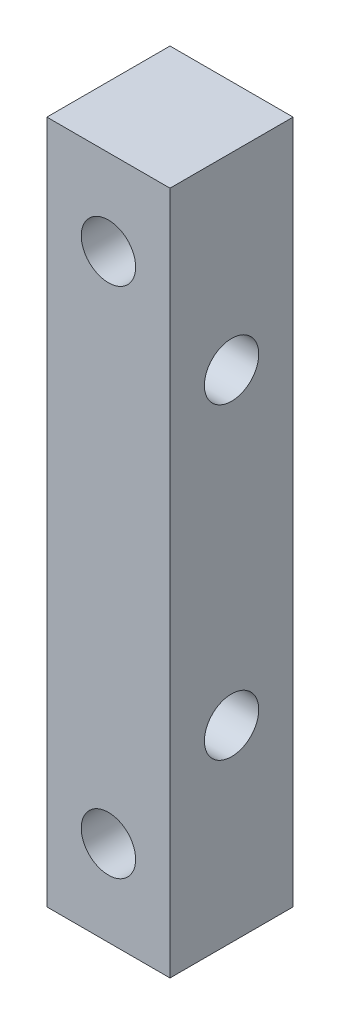
SolidWorks part; units mm, degrees
ref_plane "Front Plane" through (0, 0, 0) normal (0, 0, 1) x (1, 0, 0)
ref_plane "Top Plane" through (0, 0, 0) normal (0, 1, 0) x (1, 0, 0)
ref_plane "Right Plane" through (0, 0, 0) normal (1, 0, 0) x (0, 0, -1)
sketch "Sketch1" plane through (0, 0, 0) normal (0, 1, 0) x (1, 0, 0)
  line L1 (-4.572, 4.572) -> (4.572, 4.572)
  line L2 (-4.572, 4.572) -> (-4.572, -4.572)
  line L3 (-4.572, -4.572) -> (4.572, -4.572)
  line L4 (4.572, 4.572) -> (4.572, -4.572)
  line L5 (-4.572, 4.572) -> (4.572, -4.572) construction
  line L6 (-4.572, -4.572) -> (4.572, 4.572) construction
  point P0 (0, 0)
  dimension "D1" = 9.144
extrude "Boss-Extrude1" add sketch "Sketch1" along normal blind 50.8
sketch "Sketch3" plane through (0, 0, 4.572) normal (0, 0, 1) x (1, 0, 0)
  line L0 (0, 44.45) -> (0, 6.35) construction
  line L1 (4.572, 50.8) -> (4.572, 0) construction
  point P3 (0, 25.4)
  point P8 (4.572, 25.4)
  dimension "D1" = 38.1
hole_wizard "Tap Drill for #10-32 Tap1" positions "Sketch4" profile "Sketch6" hole size "#10-32" standard "ANSI Inch" end condition through all
sketch "Sketch4" plane through (0, 0, 4.572) normal (0, 0, 1) x (1, 0, 0)
  point P0 (0, 44.45)
  point P3 (0, 6.35)
sketch "Sketch6" plane through (0, 44.45, 4.572) normal (1, 0, 0) x (0, -1, 0)
  line L0 (0, 0) -> (0, 9.144)
  line L1 (0, 9.144) -> (2.0193, 9.144)
  line L2 (2.0193, 9.144) -> (2.0193, 0)
  line L5 (2.0193, 0) -> (0, 0)
  line L11 (0, -6.35) -> (0, 107.95) construction
  dimension "Thru Hole Dia." = 4.0386
  dimension "Thru Hole Depth" = 9.144
sketch "Sketch7" plane through (4.572, 0, 0) normal (1, 0, 0) x (0, 0, -1)
  line L0 (0, 36.83) -> (0, 13.97) construction
  line L1 (-4.572, 50.8) -> (-4.572, 0) construction
  line L2 (-4.572, 0) -> (4.572, 0) construction
  point P2 (-4.572, 25.4)
  point P3 (0, 25.4)
  point P8 (0, 0)
  dimension "D1" = 22.86
hole_wizard "Tap Drill for #10-32 Tap2" positions "Sketch10" profile "Sketch11" hole size "#10-32" standard "ANSI Inch" end condition through all
sketch "Sketch10" plane through (4.572, 0, 0) normal (1, 0, 0) x (0, 0, -1)
  point P0 (0, 36.83)
  point P3 (0, 13.97)
sketch "Sketch11" plane through (4.572, 36.83, 0) normal (0, 1, 0) x (0, 0, -1)
  line L0 (0, 0) -> (0, 9.144)
  line L1 (0, 9.144) -> (2.0193, 9.144)
  line L2 (2.0193, 9.144) -> (2.0193, 0)
  line L5 (2.0193, 0) -> (0, 0)
  line L11 (0, -6.35) -> (0, 107.95) construction
  dimension "Thru Hole Dia." = 4.0386
  dimension "Thru Hole Depth" = 9.144
